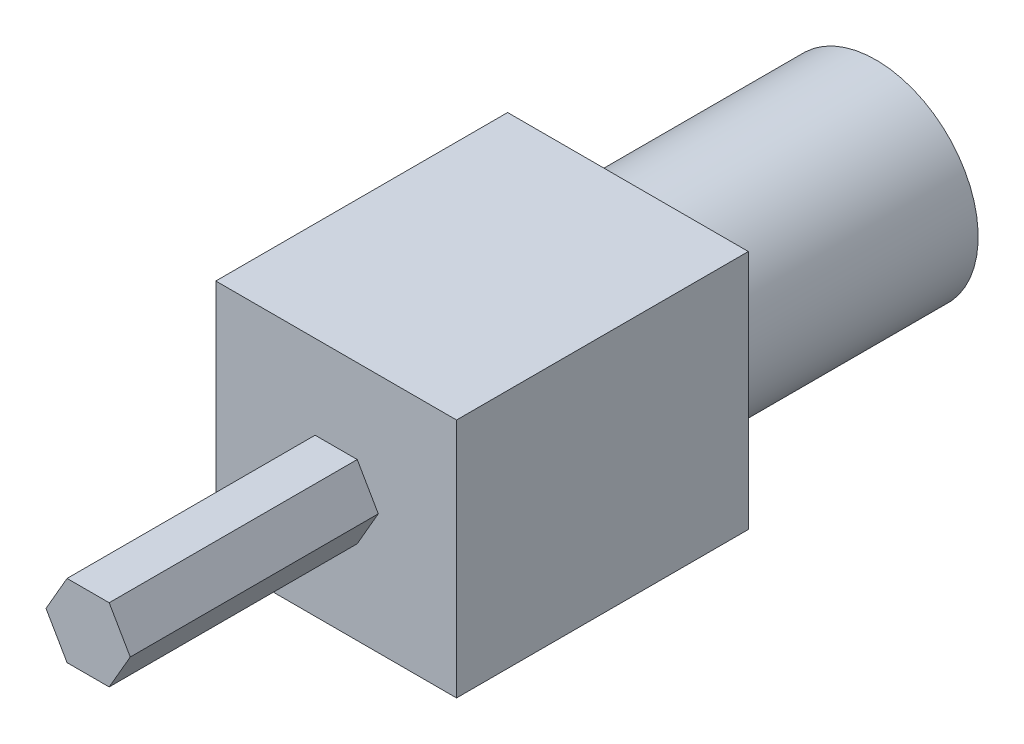
SolidWorks part; units mm, degrees
ref_plane "Front Plane" through (0, 0, 0) normal (0, 0, 1) x (1, 0, 0)
ref_plane "Top Plane" through (0, 0, 0) normal (0, 1, 0) x (1, 0, 0)
ref_plane "Right Plane" through (0, 0, 0) normal (1, 0, 0) x (0, 0, -1)
sketch "Sketch1" plane through (0, 0, 0) normal (0, 1, 0) x (1, 0, 0)
  line L1 (0, 0) -> (-41.91, 0)
  line L2 (0, 0) -> (0, 50.8)
  line L3 (0, 50.8) -> (-41.91, 50.8)
  line L4 (-41.91, 0) -> (-41.91, 50.8)
  dimension "D1" = 41.91
  dimension "D2" = 50.8
extrude "Boss-Extrude1" add sketch "Sketch1" along normal blind 41.91
sketch "Sketch2" plane through (0, 0, -50.8) normal (0, 0, -1) x (-1, 0, 0)
  line L0 (0, 41.91) -> (41.91, 41.91) construction
  line L1 (0, 41.91) -> (0, 0) construction
  circle A0 centre (20.955, 20.955) radius 17.78
  dimension "D1" = 35.56
  dimension "D2" = 20.955
  dimension "D3" = 20.955
extrude "Boss-Extrude2" add sketch "Sketch2" along normal blind 43.18
sketch "Sketch3" plane through (0, 0, 0) normal (0, 0, 1) x (1, 0, 0)
  line L0 (-41.91, 41.91) -> (0, 41.91) construction
  line L1 (-13.6227, 20.955) -> (-17.2888, 27.305)
  line L2 (-17.2888, 27.305) -> (-24.6212, 27.305)
  line L3 (-24.6212, 27.305) -> (-28.2873, 20.955)
  line L4 (-28.2873, 20.955) -> (-24.6212, 14.605)
  line L5 (-24.6212, 14.605) -> (-17.2888, 14.605)
  line L6 (-17.2888, 14.605) -> (-13.6227, 20.955)
  line L7 (-41.91, 41.91) -> (-41.91, 0) construction
  circle A0 centre (-20.955, 20.955) radius 6.35 construction
  dimension "D1" = 12.7
  dimension "D2" = 20.955
  dimension "D3" = 20.955
extrude "Boss-Extrude4" add sketch "Sketch3" along normal blind 43.18
